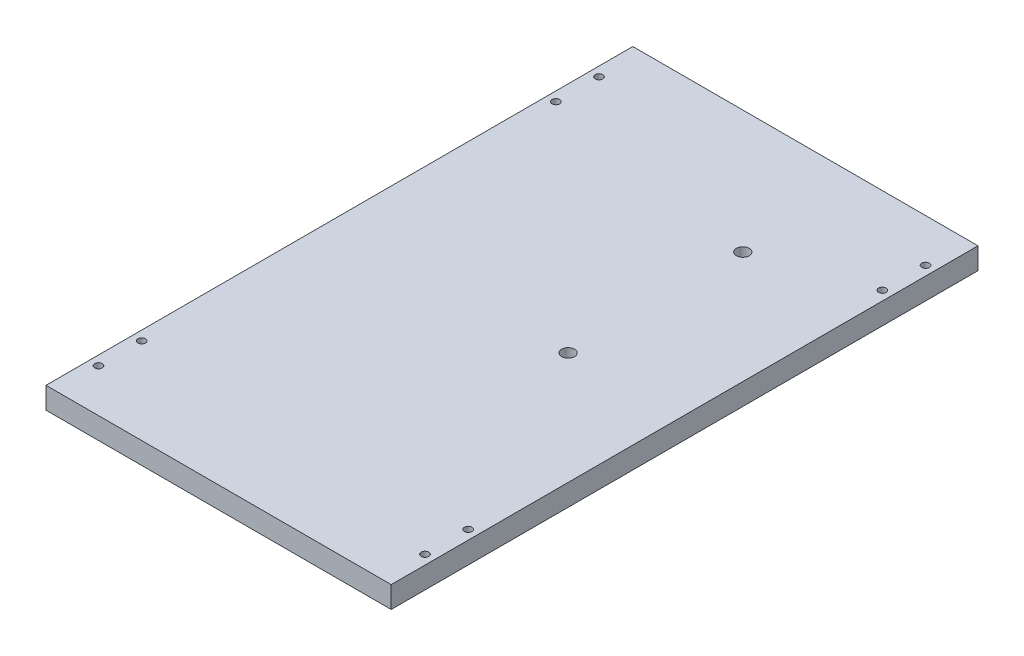
SolidWorks part; units mm, degrees
ref_plane "Front Plane" through (0, 0, 0) normal (0, 0, 1) x (1, 0, 0)
ref_plane "Top Plane" through (0, 0, 0) normal (0, 1, 0) x (1, 0, 0)
ref_plane "Right Plane" through (0, 0, 0) normal (1, 0, 0) x (0, 0, -1)
sketch "Sketch1" plane through (0, 0, 0) normal (0, 1, 0) x (1, 0, 0)
  line L0 (4.3284, 212) -> (4.3284, 272) construction
  line L1 (0, 0) -> (160, 0)
  line L2 (0, 0) -> (0, 272)
  line L3 (0, 272) -> (160, 272)
  line L4 (160, 0) -> (160, 272)
  line L5 (-0.1716, 212) -> (8.8284, 212) construction
  line L6 (80, 136) -> (80, 272) construction
  line L8 (0, 136) -> (160, 136) construction
  circle A0 centre (4.3284, 232) radius 1.75
  circle A1 centre (4.3284, 252) radius 1.75
  circle A6 centre (4.3284, 40) radius 1.75
  circle A7 centre (4.3284, 20) radius 1.75
  circle A14 centre (155.6716, 20) radius 1.75
  circle A15 centre (155.6716, 40) radius 1.75
  circle A16 centre (155.6716, 232) radius 1.75
  circle A17 centre (155.6716, 252) radius 1.75
  dimension "D3" = 3.5
  dimension "D4" = 3.5
  dimension "D6" = 20
  dimension "D1" = 160
  dimension "D2" = 272
  dimension "D5" = 20
extrude "Boss-Extrude1" add sketch "Sketch1" along normal blind 10
sketch "Sketch3" plane through (0, 10, 0) normal (0, 1, 0) x (1, 0, 0)
  line L10 (80, 272) -> (80, -13.0842) construction
  line L11 (160, 272) -> (0, 272) construction
  line L12 (80, 272) -> (153, 272) construction
  line L13 (153, 272) -> (108, 272) construction
  line L14 (108, 272) -> (108, 170) construction
  circle A0 centre (108, 134) radius 3
  circle A1 centre (108, 215) radius 3
  dimension "D1" = 57
  dimension "D2" = 138
extrude "Cut-Extrude1" cut sketch "Sketch3" against normal blind 18
